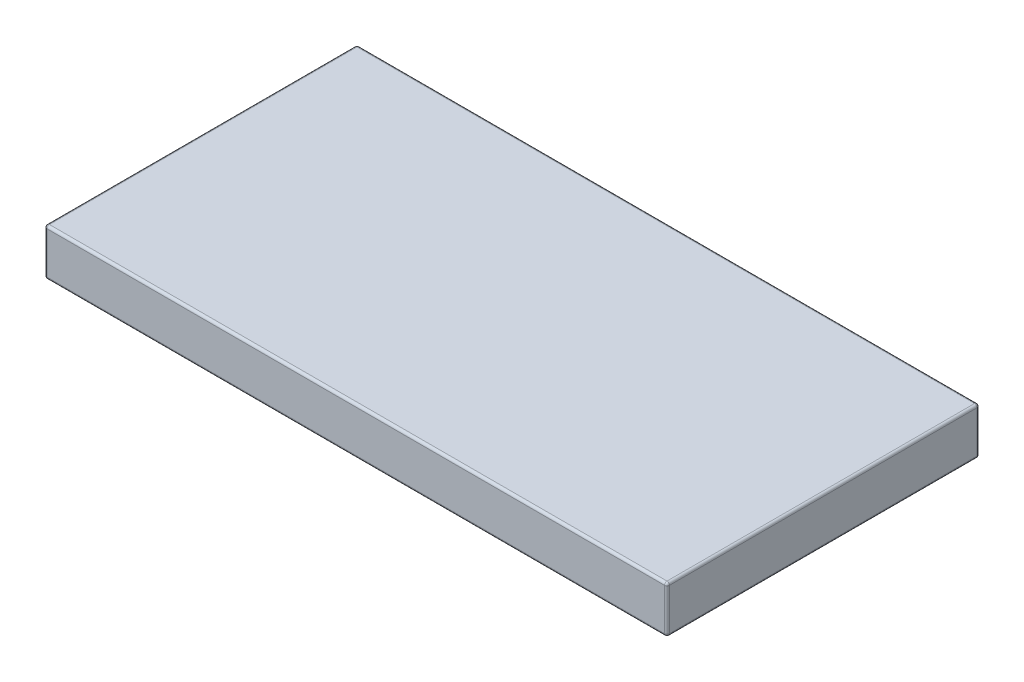
SolidWorks part; units mm, degrees
ref_plane "Front" through (0, 0, 0) normal (0, 0, 1) x (1, 0, 0)
ref_plane "Top" through (0, 0, 0) normal (0, 1, 0) x (1, 0, 0)
ref_plane "Right" through (0, 0, 0) normal (1, 0, 0) x (0, 0, -1)
sketch "Sketch1" plane through (0, 0, 0) normal (0, 1, 0) x (1, 0, 0)
  line L1 (-44.6911, 108.6322) -> (208.3089, 108.6322)
  line L2 (-44.6911, 108.6322) -> (-44.6911, -18.3678)
  line L3 (-44.6911, -18.3678) -> (208.3089, -18.3678)
  line L4 (208.3089, 108.6322) -> (208.3089, -18.3678)
  dimension "D1" = 253
  dimension "D2" = 127
extrude "Boss-Extrude1" add sketch "Sketch1" along normal blind 19
fillet "Fillet1" radius 1 12 edges at (208.3089, 9.5, -108.6322) (208.3089, 0, -45.1322) (81.8089, 0, -108.6322) (208.3089, 9.5, 18.3678) (81.8089, 0, 18.3678) (-44.6911, 9.5, -108.6322) (-44.6911, 9.5, 18.3678) (-44.6911, 0, -45.1322) (81.8089, 19, -108.6322) (208.3089, 19, -45.1322) (81.8089, 19, 18.3678) (-44.6911, 19, -45.1322)
